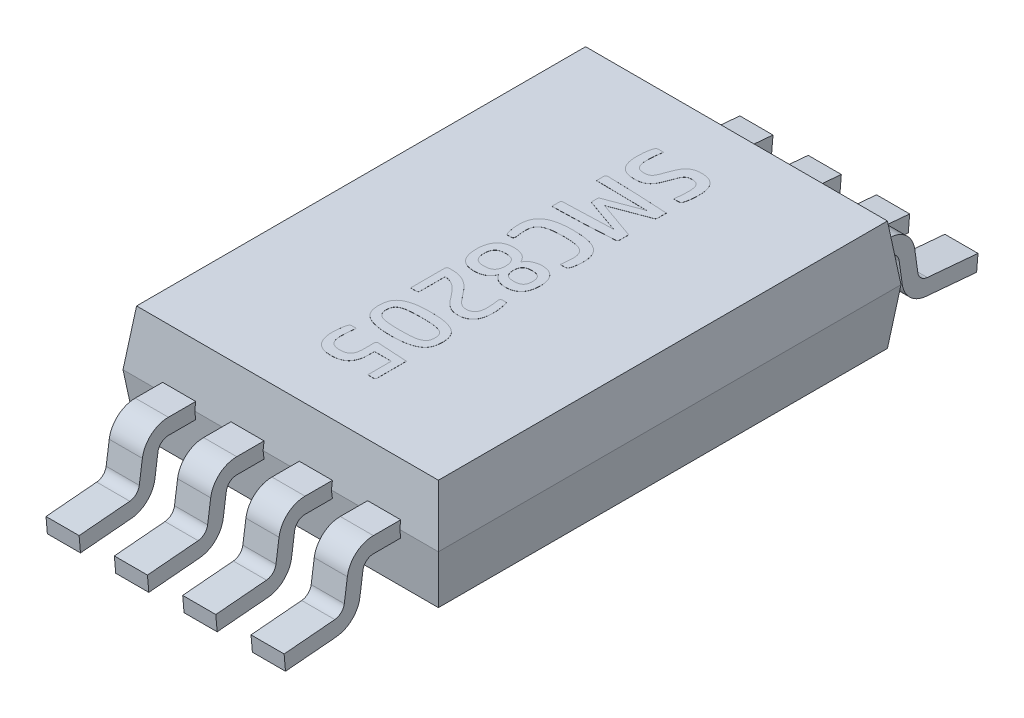
SolidWorks part; units mm, degrees
ref_plane "Front" through (0, 0, 0) normal (0, 0, 1) x (1, 0, 0)
ref_plane "Top" through (0, 0, 0) normal (0, 1, 0) x (1, 0, 0)
ref_plane "Right" through (0, 0, 0) normal (1, 0, 0) x (0, 0, -1)
sketch "Sketch1" plane through (0, 0, 0) normal (0, 1, 0) x (1, 0, 0)
  line L1 (-1.5, -2.2) -> (1.5, -2.2)
  line L2 (-1.5, -2.2) -> (-1.5, 2.2)
  line L3 (-1.5, 2.2) -> (1.5, 2.2)
  line L4 (1.5, -2.2) -> (1.5, 2.2)
  line L5 (-1.5, -2.2) -> (1.5, 2.2) construction
  line L6 (-1.5, 2.2) -> (1.5, -2.2) construction
  point P0 (0, 0)
  dimension "D1" = 3
  dimension "D2" = 4.4
extrude "Extrude1" add sketch "Sketch1" along normal mid plane 1.05 draft 7
ref_plane "Plane1" through (0.975, 0, 0) normal (1, 0, 0) x (0, 0, -1)
sketch "Sketch5" plane through (0.975, 0, 0) normal (1, 0, 0) x (0, 0, -1)
  line L0 (0, 0.075) -> (-2.451, 0.075)
  line L1 (-2.6985, -0.1402) -> (-2.7277, -0.3477)
  line L2 (-2.818, -0.4334) -> (-3.3, -0.4756)
  line L3 (-2.2, 0) -> (2.2, 0) construction
  line L4 (-2.1355, -0.525) -> (2.1355, -0.525) construction
  line L5 (-3.3, -0.4756) -> (-3.2869, -0.625)
  line L7 (0, -0.075) -> (-2.451, -0.075)
  line L8 (-2.55, -0.1611) -> (-2.5792, -0.3686)
  line L9 (-2.8049, -0.5828) -> (-3.2869, -0.625)
  line L10 (0, 0.075) -> (0, -0.075) construction
  line L11 (2.8049, -0.5828) -> (3.2869, -0.625)
  line L12 (2.55, -0.1611) -> (2.5792, -0.3686)
  line L13 (0, -0.075) -> (2.451, -0.075)
  line L14 (3.3, -0.4756) -> (3.2869, -0.625)
  line L15 (2.818, -0.4334) -> (3.3, -0.4756)
  line L16 (2.6985, -0.1402) -> (2.7277, -0.3477)
  line L17 (0, 0.075) -> (2.451, 0.075)
  arc A0 (-2.7277, -0.3477) -> (-2.818, -0.4334) centre (-2.8267, -0.3338) cw
  arc A1 (-2.451, 0.075) -> (-2.6985, -0.1402) centre (-2.451, -0.175) ccw
  arc A2 (-2.451, -0.075) -> (-2.55, -0.1611) centre (-2.451, -0.175) ccw
  arc A3 (-2.5792, -0.3686) -> (-2.8049, -0.5828) centre (-2.8267, -0.3338) cw
  arc A4 (2.5792, -0.3686) -> (2.8049, -0.5828) centre (2.8267, -0.3338) ccw
  arc A5 (2.451, -0.075) -> (2.55, -0.1611) centre (2.451, -0.175) cw
  arc A6 (2.451, 0.075) -> (2.6985, -0.1402) centre (2.451, -0.175) cw
  arc A7 (2.7277, -0.3477) -> (2.818, -0.4334) centre (2.8267, -0.3338) ccw
  arc A8 (-2.7277, -0.3477) -> (-2.818, -0.4334) centre (-2.8267, -0.3338) cw construction
  point P13 (-2.7388, -0.4265)
  dimension "D8" = 0.1
  dimension "D1" = 0.075
  dimension "D2" = 6.6
  dimension "D3" = 5
  dimension "D4" = 0.1
  dimension "D5" = 82
  dimension "D6" = 0.15
  dimension "D7" = 0.75
extrude "Extrude3" add sketch "Sketch5" along normal mid plane 0.315
pattern_linear "LPattern1" count 4 spacing 0.65 along (-1, 0, 0) of "Extrude3"
sketch "Sketch6" plane through (0, 0.525, 0) normal (0, 1, 0) x (1, 0, 0)
  line L0 (-0.2799, 2.1355) -> (-0.2799, -2.1355) construction
  line L1 (1.4355, 2.1355) -> (-1.4355, 2.1355) construction
  line L2 (-1.4355, -2.1355) -> (1.4355, -2.1355) construction
  text T0 "SMC8205" font "HP Simplified" height 0.6
extrude "Boss-Extrude1" add sketch "Sketch6" along normal blind 0.001
